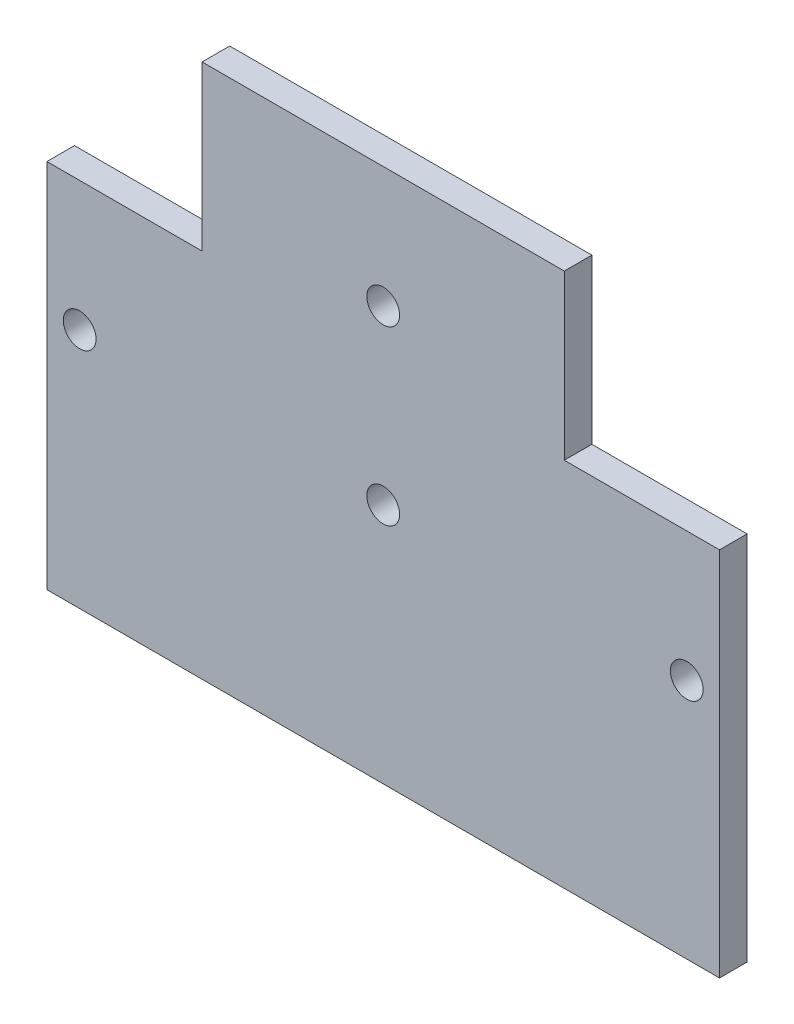
SolidWorks part; units mm, degrees
ref_plane "前视基准面" through (0, 0, 0) normal (0, 0, 1) x (1, 0, 0)
ref_plane "上视基准面" through (0, 0, 0) normal (0, 1, 0) x (1, 0, 0)
ref_plane "右视基准面" through (0, 0, 0) normal (1, 0, 0) x (0, 0, -1)
other "Configuration Table"
sketch "草图1" plane through (0, 0, 0) normal (0, 0, 1) x (1, 0, 0)
  line L0 (-19.5, 6) -> (-10.5, 6)
  line L1 (-10.5, 6) -> (-10.5, 15.5)
  line L2 (-10.5, 15.5) -> (10.5, 15.5)
  line L3 (10.5, 15.5) -> (10.5, 6)
  line L4 (10.5, 6) -> (19.5, 6)
  line L5 (19.5, 6) -> (19.5, -15.5)
  line L6 (19.5, -15.5) -> (-19.5, -15.5)
  line L7 (-19.5, -15.5) -> (-19.5, 6)
  circle A0 centre (-17.6, -1.5) radius 0.95
  circle A1 centre (0, -1.5) radius 0.95
  circle A2 centre (17.6, -1.5) radius 0.95
  circle A3 centre (0, 8.5) radius 0.95
extrude "凸台-拉伸1" add sketch "草图1" along normal blind 1.6
